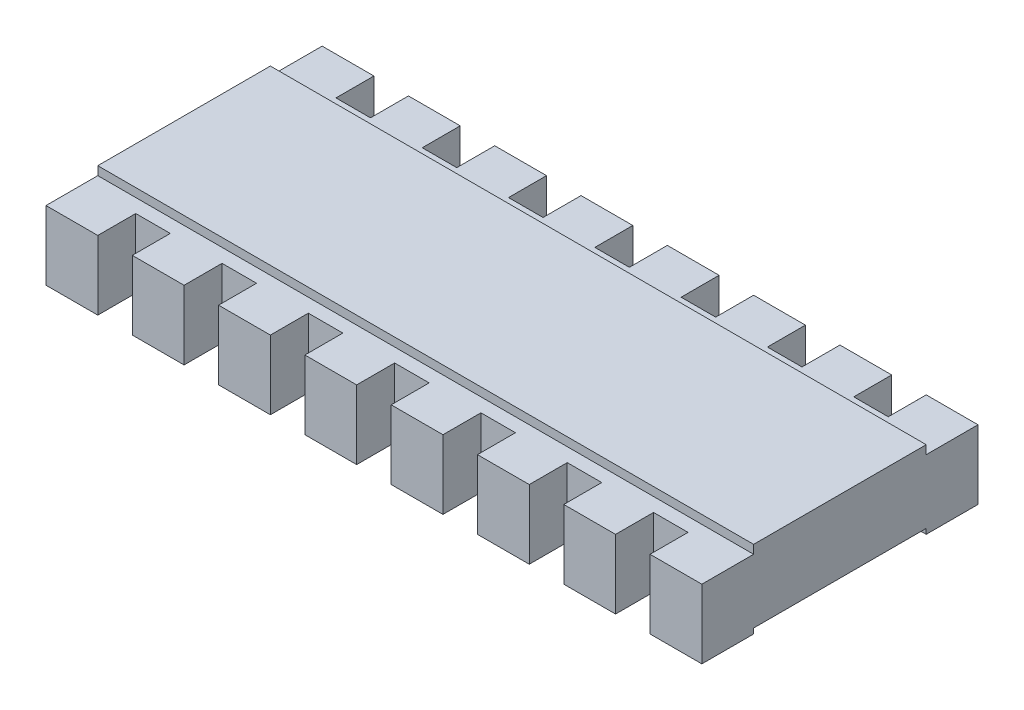
SolidWorks part; units mm, degrees
ref_plane "Front Plane" through (0, 0, 0) normal (0, 0, 1) x (1, 0, 0)
ref_plane "Top Plane" through (0, 0, 0) normal (0, 1, 0) x (1, 0, 0)
ref_plane "Right Plane" through (0, 0, 0) normal (1, 0, 0) x (0, 0, -1)
sketch "Sketch1" plane through (0, 0, 0) normal (0, 1, 0) x (1, 0, 0)
  line L1 (1.9, -0.5) -> (-1.9, -0.5)
  line L2 (1.9, -0.5) -> (1.9, 0.5)
  line L3 (1.9, 0.5) -> (-1.9, 0.5)
  line L4 (-1.9, -0.5) -> (-1.9, 0.5)
  line L5 (1.9, -0.5) -> (-1.9, 0.5) construction
  line L6 (1.9, 0.5) -> (-1.9, -0.5) construction
  point P0 (0, 0)
  dimension "D1" = 3.8
  dimension "D2" = 1
extrude "Boss-Extrude1" add sketch "Sketch1" along normal blind 0.42 from offset 0.03
sketch "Sketch2" plane through (0, 0, 0) normal (0, 1, 0) x (1, 0, 0)
  line L0 (1.9, 0.5) -> (-1.9, 0.5)
  line L1 (-1.9, 0.5) -> (-1.9, 0.8)
  line L2 (-1.9, 0.8) -> (-1.6, 0.8)
  line L3 (-1.6, 0.8) -> (-1.6, 0.58)
  line L4 (-1.6, 0.58) -> (-1.4, 0.58)
  line L5 (-1.4, 0.58) -> (-1.4, 0.8)
  line L6 (-1.4, 0.8) -> (-1.1, 0.8)
  line L7 (-1.1, 0.8) -> (-1.1, 0.58)
  line L8 (-1.1, 0.58) -> (-0.9, 0.58)
  line L9 (-0.9, 0.58) -> (-0.9, 0.8)
  line L10 (-0.9, 0.8) -> (-0.6, 0.8)
  line L11 (-0.6, 0.8) -> (-0.6, 0.58)
  line L12 (-0.6, 0.58) -> (-0.4, 0.58)
  line L13 (-0.4, 0.58) -> (-0.4, 0.8)
  line L14 (-0.4, 0.8) -> (-0.1, 0.8)
  line L15 (-0.1, 0.8) -> (-0.1, 0.58)
  line L16 (-0.1, 0.58) -> (0.1, 0.58)
  line L17 (0.1, 0.58) -> (0.1, 0.8)
  line L18 (0.1, 0.8) -> (0.4, 0.8)
  line L19 (0.4, 0.8) -> (0.4, 0.58)
  line L20 (0.4, 0.58) -> (0.6, 0.58)
  line L21 (0.6, 0.58) -> (0.6, 0.8)
  line L22 (0.6, 0.8) -> (0.9, 0.8)
  line L23 (0.9, 0.8) -> (0.9, 0.58)
  line L24 (0.9, 0.58) -> (1.1, 0.58)
  line L25 (1.1, 0.58) -> (1.1, 0.8)
  line L26 (1.1, 0.8) -> (1.4, 0.8)
  line L27 (1.4, 0.8) -> (1.4, 0.58)
  line L28 (1.4, 0.58) -> (1.6, 0.58)
  line L29 (1.6, 0.58) -> (1.6, 0.8)
  line L30 (1.6, 0.8) -> (1.9, 0.8)
  line L31 (1.9, 0.5) -> (1.9, 0.8)
  line L32 (-1.6, 0.8) -> (-1.4, 0.8) construction
  line L33 (-1.1, 0.8) -> (-0.9, 0.8) construction
  line L34 (-0.6, 0.8) -> (-0.4, 0.8) construction
  line L35 (-0.1, 0.8) -> (0.1, 0.8) construction
  line L36 (-1.4, 0.58) -> (-1.1, 0.58) construction
  line L37 (0.6, 0.8) -> (0.4, 0.8) construction
  line L38 (0.9, 0.8) -> (1.1, 0.8) construction
  line L39 (1.4, 0.8) -> (1.6, 0.8) construction
  line L40 (-0.9, 0.58) -> (-0.6, 0.58) construction
  line L41 (-0.4, 0.58) -> (-0.1, 0.58) construction
  line L42 (0.1, 0.58) -> (0.4, 0.58) construction
  line L43 (0.6, 0.58) -> (0.9, 0.58) construction
  line L44 (1.1, 0.58) -> (1.4, 0.58) construction
  point P8 (-1.75, 0.8)
  point P35 (-1.25, 0.8)
  point P36 (0, 0)
  point P37 (0, 0)
  point P39 (0, 0)
  point P40 (0, 0)
  point P41 (0, 0)
  point P42 (0, 0)
  dimension "D1" = 0.3
  dimension "D2" = 0.5
  dimension "D3" = 0.08
extrude "Boss-Extrude2" add sketch "Sketch2" along normal blind 0.4
mirror "Mirror1" about plane through (0, 0, 0) normal (0, 0, 1) of "Boss-Extrude2"
